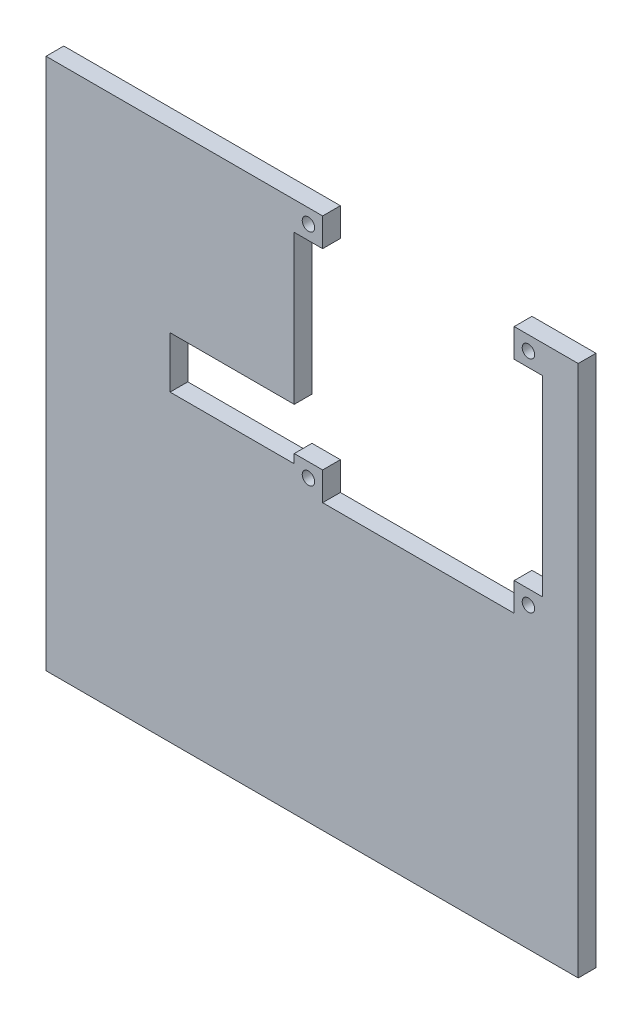
SolidWorks part; units mm, degrees
ref_plane "Front Plane" through (0, 0, 0) normal (0, 0, 1) x (1, 0, 0)
ref_plane "Top Plane" through (0, 0, 0) normal (0, 1, 0) x (1, 0, 0)
ref_plane "Right Plane" through (0, 0, 0) normal (1, 0, 0) x (0, 0, -1)
sketch "Sketch1" plane through (0, 0, 0) normal (0, 0, 1) x (1, 0, 0)
  line L1 (0, 0) -> (150, 0)
  line L2 (0, 0) -> (0, 150)
  line L3 (0, 150) -> (150, 150)
  line L4 (150, 0) -> (150, 150)
  dimension "D1" = 150
  dimension "D2" = 150
extrude "Boss-Extrude1" add sketch "Sketch1" along normal blind 5
sketch "Sketch2" plane through (0, 0, 5) normal (0, 0, 1) x (1, 0, 0)
  line L0 (77.96, 150) -> (131.96, 150)
  line L1 (131.96, 150) -> (131.96, 142)
  line L2 (131.96, 142) -> (139.96, 142)
  line L3 (139.96, 142) -> (139.96, 88)
  line L4 (139.96, 88) -> (131.96, 88)
  line L5 (131.96, 88) -> (131.96, 80)
  line L6 (131.96, 80) -> (77.96, 80)
  line L7 (77.96, 80) -> (77.96, 88)
  line L8 (77.96, 88) -> (69.96, 88)
  line L9 (69.96, 88) -> (69.96, 142)
  line L10 (69.96, 142) -> (77.96, 142)
  line L11 (77.96, 142) -> (77.96, 150)
  line L12 (77.96, 150) -> (69.96, 150) construction
  line L13 (69.96, 150) -> (69.96, 142) construction
  line L14 (69.96, 88) -> (69.96, 80) construction
  line L15 (69.96, 80) -> (77.96, 80) construction
  line L16 (131.96, 80) -> (139.96, 80) construction
  line L17 (139.96, 80) -> (139.96, 88) construction
  line L18 (139.96, 142) -> (139.96, 150) construction
  line L19 (139.96, 150) -> (131.96, 150) construction
  line L20 (73.96, 150) -> (73.96, 146) construction
  line L21 (73.96, 146) -> (69.96, 146) construction
  line L22 (73.96, 80) -> (73.96, 84) construction
  line L23 (73.96, 84) -> (69.96, 84) construction
  line L24 (150, 150) -> (0, 150) construction
  circle A0 centre (73.96, 84) radius 1.75
  circle A1 centre (73.96, 146) radius 1.75
  circle A2 centre (135.96, 146) radius 1.75
  circle A3 centre (135.96, 84) radius 1.75
  point P24 (80.8487, 121.5515)
  point P28 (141.8995, 117.3099)
  point P30 (135.96, 120.9169)
  dimension "D5" = 3.5
  dimension "D1" = 70
  dimension "D2" = 70
  dimension "D3" = 62
  dimension "D4" = 62
  dimension "D7" = 4
extrude "Cut-Extrude1" cut sketch "Sketch2" against normal through all
sketch "Sketch3" plane through (0, 0, 5) normal (0, 0, 1) x (1, 0, 0)
  line L0 (77.96, 80) -> (131.96, 80) construction
  line L1 (69.96, 85.5) -> (34.96, 85.5)
  line L2 (69.96, 85.5) -> (69.96, 100)
  line L3 (69.96, 100) -> (34.96, 100)
  line L4 (34.96, 85.5) -> (34.96, 100)
  line L5 (69.96, 142) -> (69.96, 88) construction
  point P7 (69.9854, 88)
  dimension "D1" = 20
  dimension "D2" = 14.5
  dimension "D3" = 35
extrude "Cut-Extrude2" cut sketch "Sketch3" against normal through all
